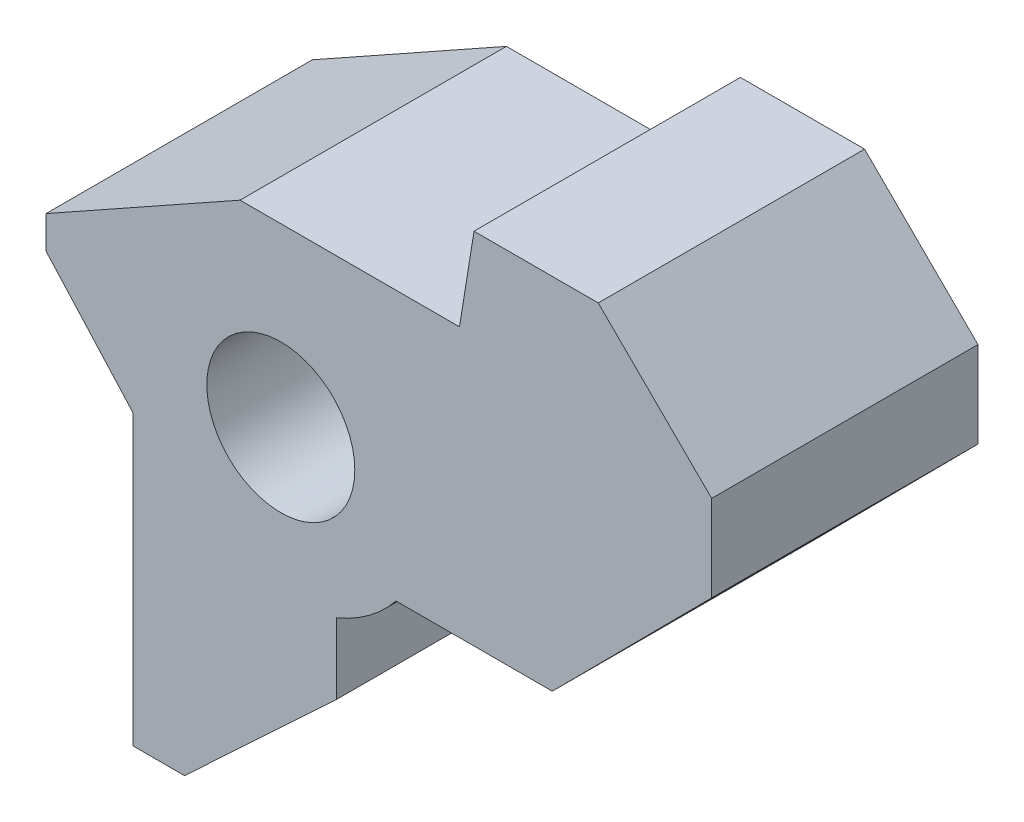
SolidWorks part; units mm, degrees
ref_plane "정면" through (0, 0, 0) normal (0, 0, 1) x (1, 0, 0)
ref_plane "윗면" through (0, 0, 0) normal (0, 1, 0) x (1, 0, 0)
ref_plane "우측면" through (0, 0, 0) normal (1, 0, 0) x (0, 0, -1)
sketch "스케치1" plane through (0, 0, 0) normal (0, 0, 1) x (1, 0, 0)
  line L0 (-5, -2.0664) -> (-7.9333, 1.1882)
  line L1 (6.0379, 5.9574) -> (6.5286, 9.0015)
  line L2 (6.5286, 9.0015) -> (10.7256, 9.0015)
  line L3 (10.7256, 9.0015) -> (14.5571, 5.198)
  line L4 (14.5571, 5.198) -> (14.5571, 2.2863)
  line L5 (14.5571, 2.2863) -> (9.173, -3.1374)
  line L6 (9.173, -3.1374) -> (3.8932, -3.1374)
  line L7 (1.8761, -4.6347) -> (1.8761, -7.0314)
  line L8 (-3.2535, -11.8209) -> (-5, -11.8209)
  line L9 (-5, -11.8209) -> (-5, -2.0664)
  line L10 (-3.2535, -11.8209) -> (1.8761, -7.0314)
  line L11 (6.0379, 5.9574) -> (-1.3764, 5.9574)
  line L13 (-7.9333, 1.1882) -> (-7.9333, 2.2863)
  line L14 (-7.9333, 2.2863) -> (-1.3764, 5.9574)
  circle A0 centre (0, 0) radius 2.5
  circle A1 centre (0, 0) radius 5
  dimension "D1" = 5
  dimension "D2" = 10
extrude "보스-돌출1" add sketch "스케치1" along normal blind 9
